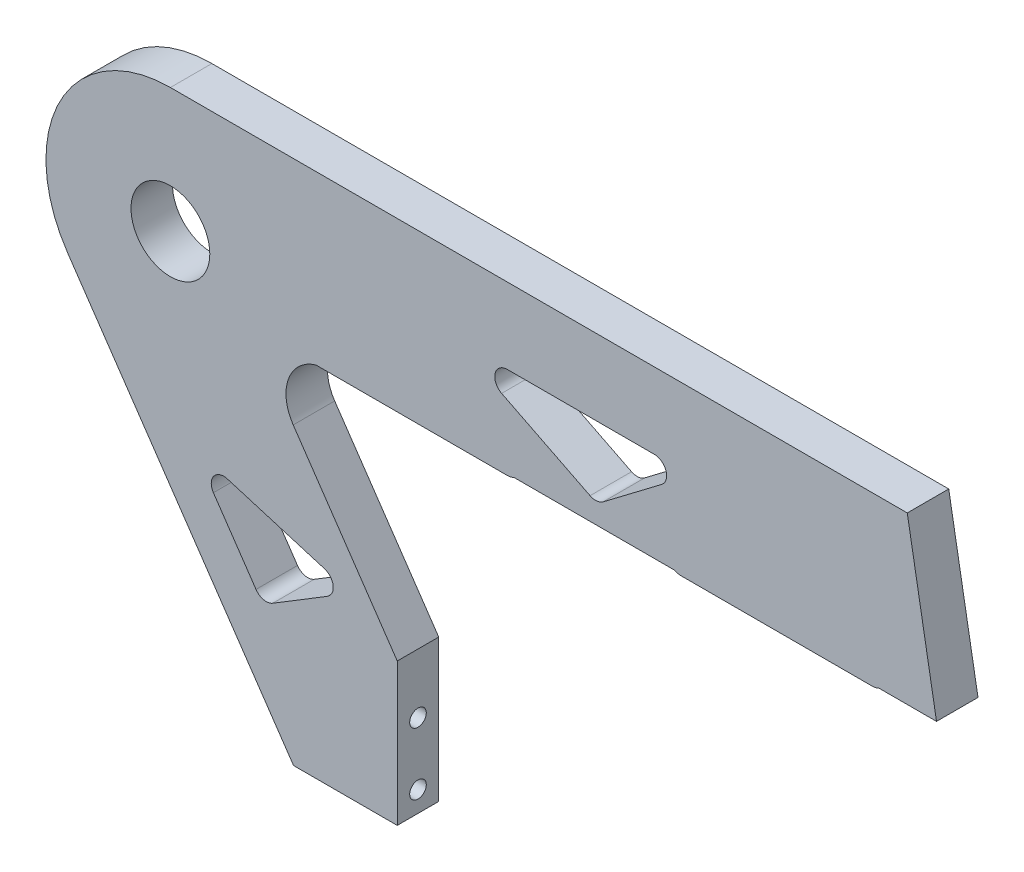
SolidWorks part; units mm, degrees
ref_plane "Front Plane" through (0, 0, 0) normal (0, 0, 1) x (1, 0, 0)
ref_plane "Top Plane" through (0, 0, 0) normal (0, 1, 0) x (1, 0, 0)
ref_plane "Right Plane" through (0, 0, 0) normal (1, 0, 0) x (0, 0, -1)
sketch "Sketch1" plane through (0, 0, 0) normal (0, 0, 1) x (1, 0, 0)
  line L0 (0, 0) -> (-25, 0)
  line L1 (-25, 0) -> (-79.4657, 79.8008)
  line L2 (-54.687, 126.7128) -> (122.9469, 126.7128)
  line L3 (122.9469, 126.7128) -> (130, 86.7128)
  line L4 (130, 86.7128) -> (-16.8223, 86.7128)
  line L5 (-25.0818, 71.0755) -> (0, 34.3267)
  line L6 (0, 34.3267) -> (0, 0)
  line L7 (0, 30) -> (150, 30) construction
  line L8 (150, 30) -> (150, -13.554) construction
  line L9 (140, 14.2228) -> (140, 30) construction
  line L10 (140, 30) -> (116.1596, 165.2058) construction
  line L17 (88.0772, 105.9373) -> (115.964, 92.0091)
  line L18 (114.6235, 86.3252) -> (68.3536, 86.3252)
  line L19 (66.5419, 91.7164) -> (84.9251, 105.6446)
  line L20 (-0.0165, 106.0397) -> (27.9502, 92.0066)
  line L21 (26.6047, 86.3252) -> (-19.6652, 86.3252)
  line L22 (-21.4905, 91.706) -> (-3.1873, 105.7391)
  line L26 (26.5057, 108.4605) -> (61.9455, 108.4605)
  line L27 (63.7572, 103.0693) -> (49.6374, 92.3714)
  line L28 (46.4803, 92.0812) -> (25.1602, 102.7791)
  line L29 (-44.3201, 47.3006) -> (-34.0482, 32.2506)
  line L30 (-30.0093, 31.3799) -> (-16.8655, 39.389)
  line L31 (-17.5627, 44.8238) -> (-40.9784, 51.8647)
  arc A0 (-79.4657, 79.8008) -> (-54.687, 126.7128) centre (-54.687, 96.7128) cw
  arc A1 (-16.8223, 86.7128) -> (-25.0818, 71.0755) centre (-16.8223, 76.7128) ccw
  circle A2 centre (-54.687, 96.7128) radius 9.5
  arc A9 (115.964, 92.0091) -> (114.6235, 86.3252) centre (114.6235, 89.3252) cw
  arc A10 (68.3536, 86.3252) -> (66.5419, 91.7164) centre (68.3536, 89.3252) cw
  arc A11 (88.0772, 105.9373) -> (84.9251, 105.6446) centre (86.7368, 103.2534) ccw
  arc A12 (27.9502, 92.0066) -> (26.6047, 86.3252) centre (26.6047, 89.3252) cw
  arc A13 (-19.6652, 86.3252) -> (-21.4905, 91.706) centre (-19.6652, 89.3252) cw
  arc A14 (-0.0165, 106.0397) -> (-3.1873, 105.7391) centre (-1.362, 103.3583) ccw
  arc A18 (49.6374, 92.3714) -> (46.4803, 92.0812) centre (47.8257, 94.7626) cw
  arc A19 (61.9455, 108.4605) -> (63.7572, 103.0693) centre (61.9455, 105.4605) cw
  arc A20 (26.5057, 108.4605) -> (25.1602, 102.7791) centre (26.5057, 105.4605) ccw
  arc A21 (-34.0482, 32.2506) -> (-30.0093, 31.3799) centre (-31.5703, 33.9418) ccw
  arc A22 (-16.8655, 39.389) -> (-17.5627, 44.8238) centre (-18.4265, 41.9508) ccw
  arc A23 (-44.3201, 47.3006) -> (-40.9784, 51.8647) centre (-41.8423, 48.9918) cw
  dimension "D10" = 30
  dimension "D11" = 10
  dimension "D12" = 19
  dimension "D13" = 3
  dimension "D14" = 3
  dimension "D2" = 40
  dimension "D3" = 40
  dimension "D4" = 30
  dimension "D5" = 25
  dimension "D6" = 150
  dimension "D7" = 10
  dimension "D8" = 130
  dimension "D9" = 80
extrude "Boss-Extrude2" add sketch "Sketch1" along normal mid plane 10
sketch "Sketch2" plane through (0, 0, 0) normal (1, 0, 0) x (0, 0, -1)
  circle A0 centre (0, 5) radius 2
  circle A1 centre (0, 20) radius 2
  dimension "D1" = 4
  dimension "D2" = 4
  dimension "D3" = 5
  dimension "D4" = 15
extrude "Cut-Extrude1" cut sketch "Sketch2" against normal mid plane 87
